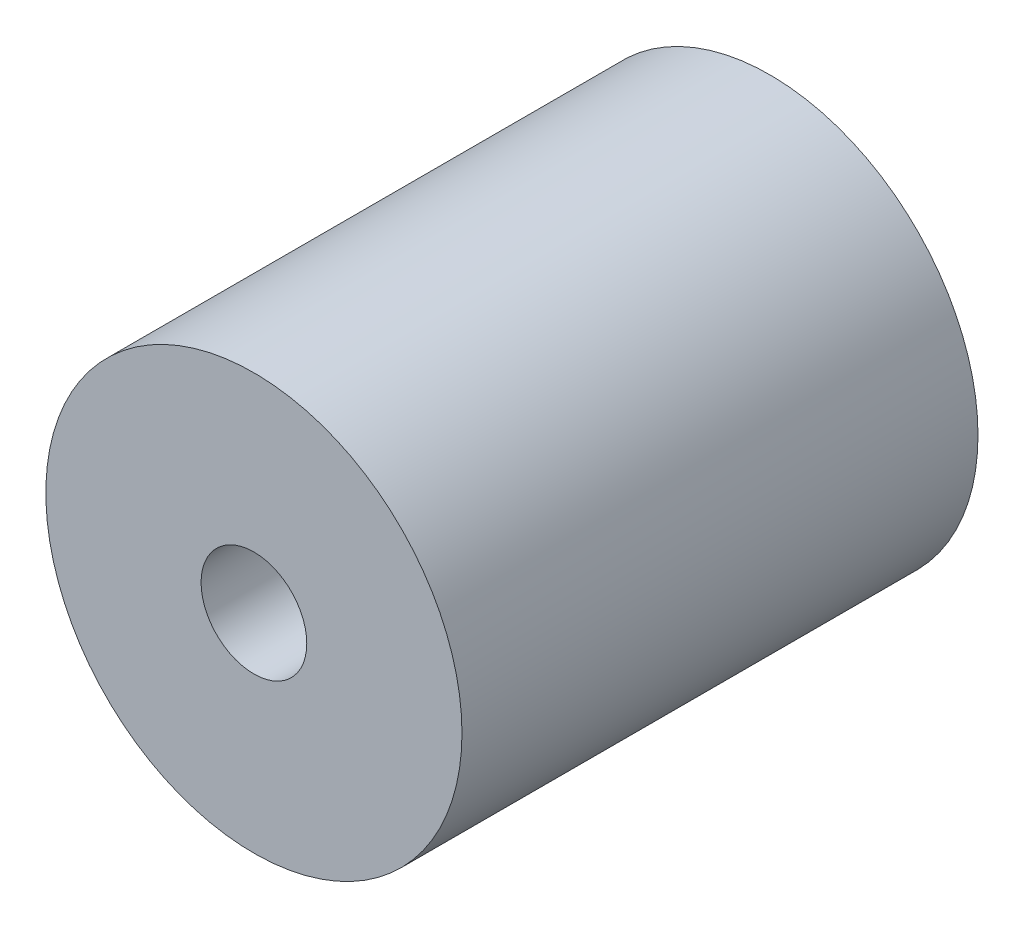
SolidWorks part; units mm, degrees
material "SKD11淬火HRC56-60"
ref_plane "前基準面" through (0, 0, 0) normal (0, 0, 1) x (1, 0, 0)
ref_plane "上基準面" through (0, 0, 0) normal (0, 1, 0) x (1, 0, 0)
ref_plane "右基準面" through (0, 0, 0) normal (1, 0, 0) x (0, 0, -1)
sketch "草图1" plane through (0, 0, 0) normal (0, 0, 1) x (1, 0, 0)
  circle A0 centre (0, 0) radius 12.5
  circle A1 centre (0, 0) radius 3.175
  dimension "D1" = 6.35
  dimension "D2" = 25
extrude "凸台-拉伸1" add sketch "草图1" along normal blind 31
sketch "草图3" plane through (0, 0, 0) normal (0, 0, -1) x (-1, 0, 0)
  circle A0 centre (0, 0) radius 5
  dimension "D1" = 10
extrude "切除-拉伸1" cut sketch "草图3" against normal blind 8
